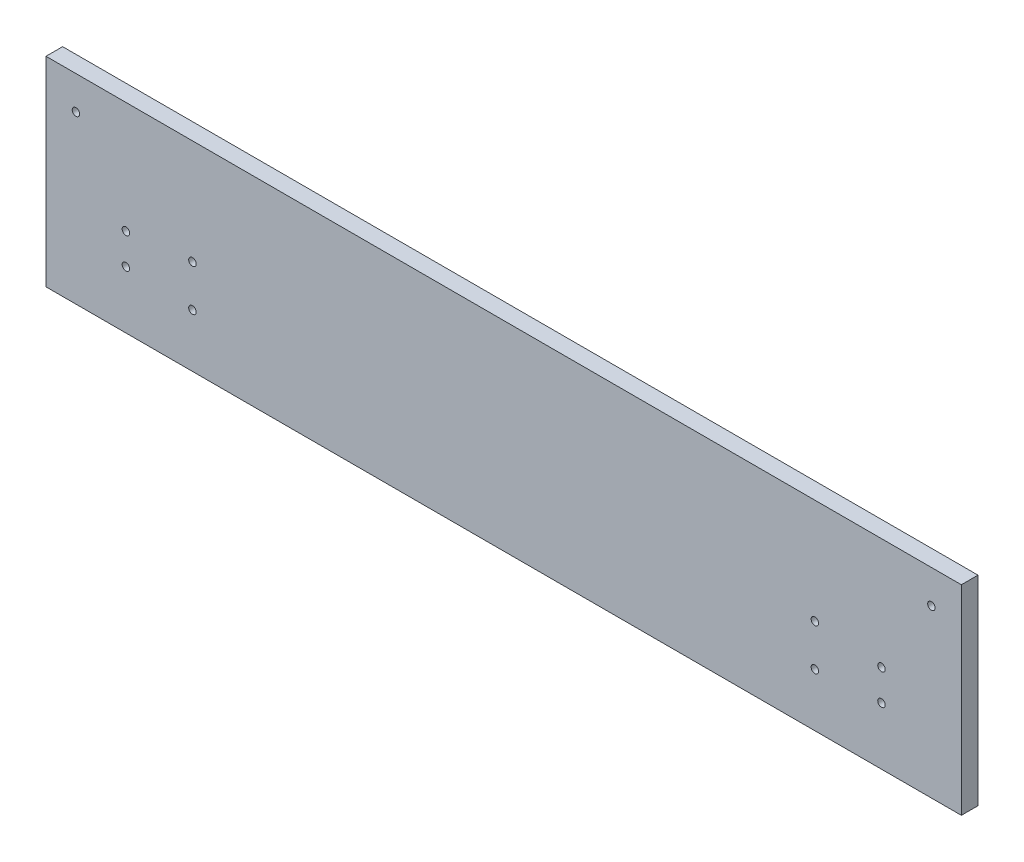
SolidWorks part; units mm, degrees
material "Multistrato di pioppo"
ref_plane "Piano frontale" through (0, 0, 0) normal (0, 0, 1) x (1, 0, 0)
ref_plane "Piano superiore" through (0, 0, 0) normal (0, 1, 0) x (1, 0, 0)
ref_plane "Piano destro" through (0, 0, 0) normal (1, 0, 0) x (0, 0, -1)
sketch "Schizzo1" plane through (0, 0, 0) normal (0, 0, 1) x (1, 0, 0)
  line L1 (-275, 60) -> (275, 60)
  line L2 (-275, 60) -> (-275, -60)
  line L3 (-275, -60) -> (275, -60)
  line L4 (275, 60) -> (275, -60)
  line L5 (-275, 60) -> (275, -60) construction
  line L6 (-275, -60) -> (275, 60) construction
  point P4 (0, 0)
  dimension "D1" = 550
  dimension "D2" = 120
extrude "Estrusione-Estrusione1" add sketch "Schizzo1" along normal blind 10
sketch "Schizzo2" plane through (0, 0, 10) normal (0, 0, 1) x (1, 0, 0)
  line L0 (183, -2) -> (183, -25) construction
  line L1 (275, -60) -> (275, 60) construction
  line L2 (-275, -60) -> (275, -60) construction
  line L3 (-183, -25) -> (-183, -2) construction
  line L4 (-275, 60) -> (-275, -60) construction
  circle A0 centre (-227, -7) radius 2.25
  circle A1 centre (-227, -25.5) radius 2.25
  circle A2 centre (227, -7) radius 2.25
  circle A3 centre (227, -25.5) radius 2.25
  circle A5 centre (-257, 40) radius 2.25
  circle A7 centre (257, 40) radius 2.25
  circle A8 centre (183, -25) radius 2.25 construction
  circle A9 centre (183, -2) radius 2.25 construction
  circle A10 centre (-183, -2) radius 2.25 construction
  circle A11 centre (-183, -25) radius 2.25 construction
  dimension "D1" = 4.5
  dimension "D2" = 23
  dimension "D3" = 92
  dimension "D4" = 58
  dimension "D5" = 92
  dimension "D6" = 58
extrude "Taglio-Estrusione1" cut sketch "Schizzo2" against normal blind 10
sketch "Schizzo3" plane through (0, 0, 0) normal (0, 0, -1) x (-1, 0, 0)
  line L0 (275, 60) -> (275, -60) construction
  line L1 (187, -28) -> (187, -3) construction
  line L2 (275, -60) -> (-275, -60) construction
  line L3 (-187, -28) -> (-187, -3) construction
  line L4 (-275, -60) -> (-275, 60) construction
  circle A1 centre (187, -28) radius 2.25
  circle A2 centre (187, -3) radius 2.25
  circle A3 centre (-187, -3) radius 2.25
  circle A4 centre (-187, -28) radius 2.25
  dimension "D2" = 4.5
  dimension "D1" = 88
  dimension "D3" = 25
  dimension "D4" = 32
  dimension "D5" = 32
  dimension "D6" = 88
  dimension "D7" = 25
extrude "Taglio-Estrusione2" cut sketch "Schizzo3" against normal blind 10
